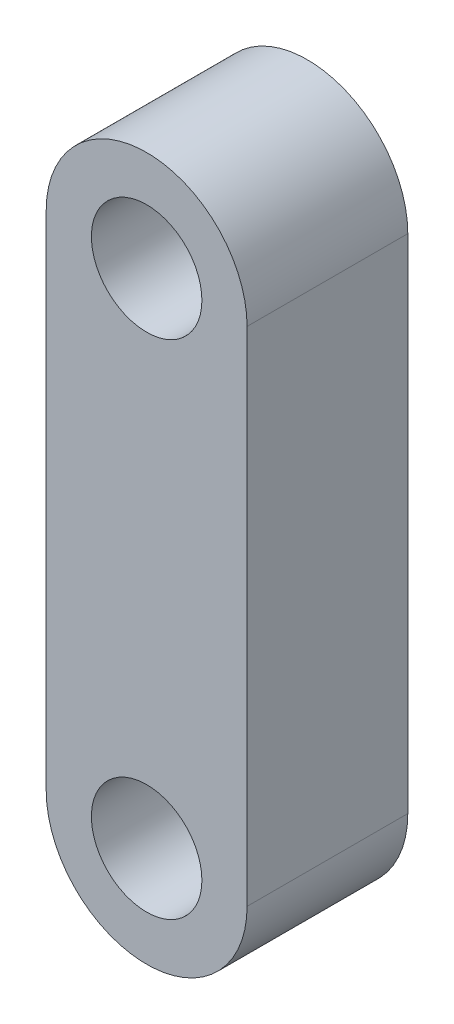
SolidWorks part; units mm, degrees
ref_plane "Front Plane" through (0, 0, 0) normal (0, 0, 1) x (1, 0, 0)
ref_plane "Top Plane" through (0, 0, 0) normal (0, 1, 0) x (1, 0, 0)
ref_plane "Right Plane" through (0, 0, 0) normal (1, 0, 0) x (0, 0, -1)
sketch "Sketch1" plane through (0, 0, 0) normal (0, 0, 1) x (1, 0, 0)
  line L2 (-29.24, 12.5) -> (-29.24, -12.5)
  line L3 (-19.24, -12.5) -> (-19.24, 12.5)
  line L4 (-29.24, 12.5) -> (-29.24, -12.5)
  line L5 (-19.24, -12.5) -> (-19.24, 12.5)
  circle A1 centre (-24.24, -12.5) radius 2.1 construction
  circle A2 centre (-24.24, 12.5) radius 2.6 construction
  circle A3 centre (-24.24, 12.5) radius 2.1 construction
  circle A4 centre (-24.24, -12.5) radius 2.6 construction
  arc A6 (-19.24, 12.5) -> (-29.24, 12.5) centre (-24.24, 12.5) ccw
  arc A7 (-29.24, -12.5) -> (-19.24, -12.5) centre (-24.24, -12.5) ccw
  arc A8 (-19.24, 12.5) -> (-29.24, 12.5) centre (-24.24, 12.5) ccw
  arc A9 (-29.24, -12.5) -> (-19.24, -12.5) centre (-24.24, -12.5) ccw
  dimension "D1" = 5.2
  dimension "5.2" = 5.2
  dimension "D3" = 0
extrude "Boss-Extrude1" add sketch "Sketch1" along normal blind 8
sketch "Sketch4" plane through (0, 0, 8) normal (0, 0, 1) x (1, 0, 0)
  point P0 (-24.24, -12.5)
  point P3 (-24.24, 12.5)
  point P8 (0, 0)
  point P9 (-24.24, 12.5)
hole_wizard "M5 Clearance Hole1" positions "Sketch4" profile "Sketch5" hole size "M5" standard "ANSI Metric" end condition through all
sketch "Sketch5" plane through (-24.24, -12.5, 8) normal (1, 0, 0) x (0, -1, 0)
  line L0 (0, 0) -> (0, 8)
  line L1 (0, 8) -> (2.75, 8)
  line L2 (2.75, 8) -> (2.75, 0)
  line L5 (2.75, 0) -> (0, 0)
  line L11 (0, -6.35) -> (0, 107.95) construction
  dimension "Thru Hole Dia." = 5.5
  dimension "Thru Hole Depth" = 8
